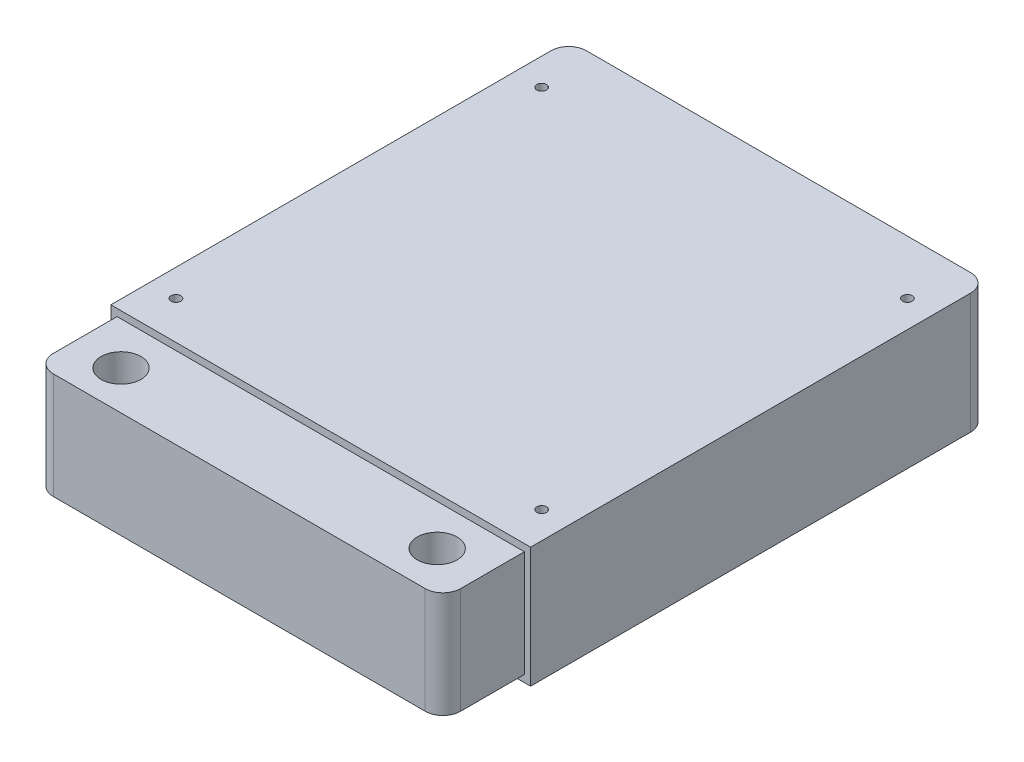
SolidWorks part; units mm, degrees
ref_plane "Front Plane" through (0, 0, 0) normal (0, 0, 1) x (1, 0, 0)
ref_plane "Top Plane" through (0, 0, 0) normal (0, 1, 0) x (1, 0, 0)
ref_plane "Right Plane" through (0, 0, 0) normal (1, 0, 0) x (0, 0, -1)
sketch "Sketch1" plane through (0, 0, 0) normal (0, 1, 0) x (1, 0, 0)
  line L2 (-143.4336, 119.2248) -> (-23.0376, 119.2248)
  line L3 (-143.4336, 119.2248) -> (-143.4336, -12.0932)
  line L4 (-143.4336, -12.0932) -> (-23.0376, -12.0932)
  line L5 (-23.0376, 119.2248) -> (-23.0376, -12.0932)
  line L6 (-143.4336, 119.2248) -> (-23.0376, -12.0932) construction
  line L7 (-143.4336, -12.0932) -> (-23.0376, 119.2248) construction
  point P2 (-83.2356, 53.5658)
  dimension "D1" = 120.396
  dimension "D2" = 131.318
extrude "Boss-Extrude1" add sketch "Sketch1" along normal blind 34.544
sketch "Sketch2" plane through (0, 34.544, 0) normal (0, 1, 0) x (1, 0, 0)
  line L0 (-143.4336, 103.7308) -> (-23.0376, 103.7308) construction
  line L1 (-143.4336, 119.2248) -> (-143.4336, -12.0932) construction
  line L2 (-23.0376, -12.0932) -> (-23.0376, 119.2248) construction
  line L3 (-143.4336, -1.1712) -> (-23.0376, -1.1712) construction
  line L4 (-135.6866, 119.2248) -> (-135.6866, -12.0932) construction
  line L5 (-23.0376, 119.2248) -> (-143.4336, 119.2248) construction
  line L6 (-143.4336, -12.0932) -> (-23.0376, -12.0932) construction
  line L7 (-30.7846, 119.2248) -> (-30.7846, -12.0932) construction
  circle A0 centre (-135.6866, 103.7308) radius 1.397
  circle A1 centre (-30.7846, 103.7308) radius 1.397
  circle A2 centre (-135.6866, -1.1712) radius 1.397
  circle A3 centre (-30.7846, -1.1712) radius 1.397
  dimension "D1" = 15.494
  dimension "D2" = 104.902
  dimension "D3" = 104.902
  dimension "D4" = 7.747
extrude "Cut-Extrude1" cut sketch "Sketch2" against normal through all
sketch "Sketch3" plane through (0, 0, 12.0932) normal (0, 0, 1) x (1, 0, 0)
  line L0 (-143.4336, 17.272) -> (-23.0376, 17.272) construction
  line L1 (-143.4336, 34.544) -> (-143.4336, 0) construction
  line L2 (-23.0376, 34.544) -> (-23.0376, 0) construction
  line L3 (-83.2356, 34.544) -> (-83.2356, 0) construction
  line L4 (-143.4336, 34.544) -> (-23.0376, 34.544) construction
  line L5 (-143.4336, 0) -> (-23.0376, 0) construction
  line L7 (-141.6556, 2.032) -> (-24.8156, 2.032)
  line L8 (-141.6556, 2.032) -> (-141.6556, 32.512)
  line L9 (-141.6556, 32.512) -> (-24.8156, 32.512)
  line L10 (-24.8156, 2.032) -> (-24.8156, 32.512)
  line L11 (-141.6556, 2.032) -> (-24.8156, 32.512) construction
  line L12 (-141.6556, 32.512) -> (-24.8156, 2.032) construction
  point P12 (-83.2356, 17.272)
  dimension "D1" = 116.84
  dimension "D2" = 30.48
extrude "Boss-Extrude2" add sketch "Sketch3" along normal blind 23.368
sketch "Sketch4" plane through (0, 32.512, 0) normal (0, 1, 0) x (1, 0, 0)
  line L0 (-128.3206, -35.4612) -> (-128.3206, -12.0932) construction
  line L1 (-24.8156, -35.4612) -> (-141.6556, -35.4612) construction
  line L2 (-24.8156, -12.0932) -> (-141.6556, -12.0932) construction
  line L3 (-38.1506, -35.4612) -> (-38.1506, -12.0932) construction
  line L4 (-141.6556, -23.6502) -> (-24.8156, -23.6502) construction
  line L5 (-141.6556, -35.4612) -> (-141.6556, -12.0932) construction
  line L6 (-24.8156, -35.4612) -> (-24.8156, -12.0932) construction
  circle A0 centre (-128.3206, -24.2882) radius 5.715
  circle A1 centre (-38.1506, -23.7772) radius 5.715
  dimension "D1" = 13.335
  dimension "D2" = 11.811
  dimension "D3" = 13.335
extrude "Cut-Extrude2" cut sketch "Sketch4" against normal through all
fillet "Fillet1" radius 5.08 4 edges at (-23.0376, 17.272, -119.2248) (-143.4336, 17.272, -119.2248) (-141.6556, 17.272, 35.4612) (-24.8156, 17.272, 35.4612)
